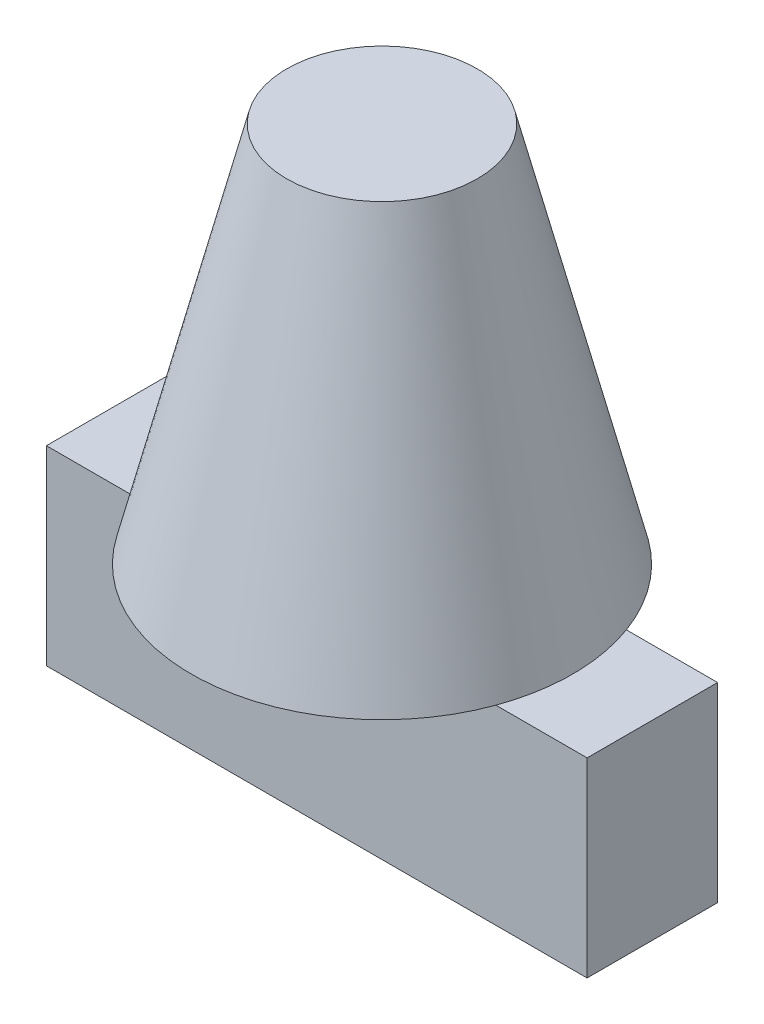
SolidWorks part; units mm, degrees
ref_plane "Front Plane" through (0, 0, 0) normal (0, 0, 1) x (1, 0, 0)
ref_plane "Top Plane" through (0, 0, 0) normal (0, 1, 0) x (1, 0, 0)
ref_plane "Right Plane" through (0, 0, 0) normal (1, 0, 0) x (0, 0, -1)
sketch "Sketch1" plane through (0, 0, 0) normal (0, 1, 0) x (1, 0, 0)
  circle A0 centre (0, 0) radius 10
  dimension "D1" = 20
ref_plane "Plane1" through (0, 20, 0) normal (0, 1, 0) x (1, 0, 0)
sketch "Sketch2" plane through (0, 20, 0) normal (0, 1, 0) x (1, 0, 0)
  circle A1 centre (0, 0) radius 5
loft "Loft1" add profiles "Sketch2", "Sketch1"
sketch "Sketch3" plane through (0, 0, 0) normal (0, -1, 0) x (1, 0, 0)
  line L1 (-14.1809, -3.4225) -> (14.1809, -3.4225)
  line L2 (-14.1809, -3.4225) -> (-14.1809, 3.4225)
  line L3 (-14.1809, 3.4225) -> (14.1809, 3.4225)
  line L4 (14.1809, -3.4225) -> (14.1809, 3.4225)
  line L5 (-14.1809, -3.4225) -> (14.1809, 3.4225) construction
  line L6 (-14.1809, 3.4225) -> (14.1809, -3.4225) construction
  point P0 (0, 0)
extrude "Boss-Extrude1" add sketch "Sketch3" along normal blind 10
